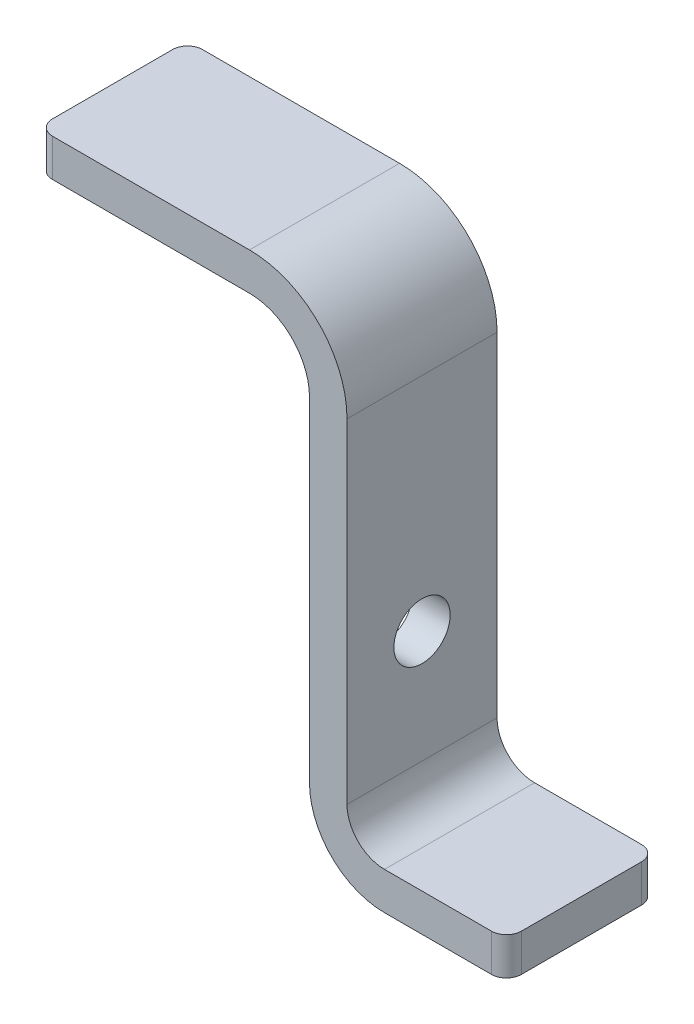
SolidWorks part; units mm, degrees
material "Alloy Steel"
ref_plane "Front Plane" through (0, 0, 0) normal (0, 0, 1) x (1, 0, 0)
ref_plane "Top Plane" through (0, 0, 0) normal (0, 1, 0) x (1, 0, 0)
ref_plane "Right Plane" through (0, 0, 0) normal (1, 0, 0) x (0, 0, -1)
other "Configuration Table"
sketch "Sketch1" plane through (0, 0, 0) normal (0, 0, 1) x (1, 0, 0)
  line L0 (0, 32.3836) -> (35.8775, 32.3836)
  line L1 (0, -55) -> (0, 55) construction
  line L2 (46.0375, 22.2236) -> (46.0375, -34.2914)
  line L3 (58.7375, -46.9914) -> (79.375, -46.9914)
  line L4 (0, 38.7336) -> (35.8775, 38.7336)
  line L5 (52.3875, 22.2236) -> (52.3875, -34.2914)
  line L6 (58.7375, -40.6414) -> (79.375, -40.6414)
  line L7 (79.375, -46.9914) -> (79.375, -40.6414)
  line L8 (0, 32.3836) -> (0, 38.7336)
  arc A0 (35.8775, 32.3836) -> (46.0375, 22.2236) centre (35.8775, 22.2236) cw
  arc A1 (46.0375, -34.2914) -> (58.7375, -46.9914) centre (58.7375, -34.2914) ccw
  arc A2 (35.8775, 38.7336) -> (52.3875, 22.2236) centre (35.8775, 22.2236) cw
  arc A3 (52.3875, -34.2914) -> (58.7375, -40.6414) centre (58.7375, -34.2914) ccw
  dimension "D5" = 10.16
  dimension "D6" = 12.7
  dimension "D2" = 85.725
  dimension "D3" = 33.3375
  dimension "D4" = 52.3875
  dimension "D1" = 6.35
extrude "Boss-Extrude1" add sketch "Sketch1" against normal blind 25.4
fillet "Fillet1" radius 2.54 4 edges at (0, 35.5586, -25.4) (0, 35.5586, 0) (79.375, -43.8164, -25.4) (79.375, -43.8164, 0)
sketch "Sketch2" plane through (52.3875, 0, 0) normal (1, 0, 0) x (0, 0, -1)
  line L0 (0, -34.2914) -> (0, 22.2236) construction
  line L1 (22.86, -46.9914) -> (2.54, -46.9914) construction
  circle A0 centre (12.7, -15.2414) radius 4.7625
  dimension "D1" = 9.525
  dimension "D2" = 12.7
  dimension "D3" = 31.75
extrude "Cut-Extrude1" cut sketch "Sketch2" against normal through all
